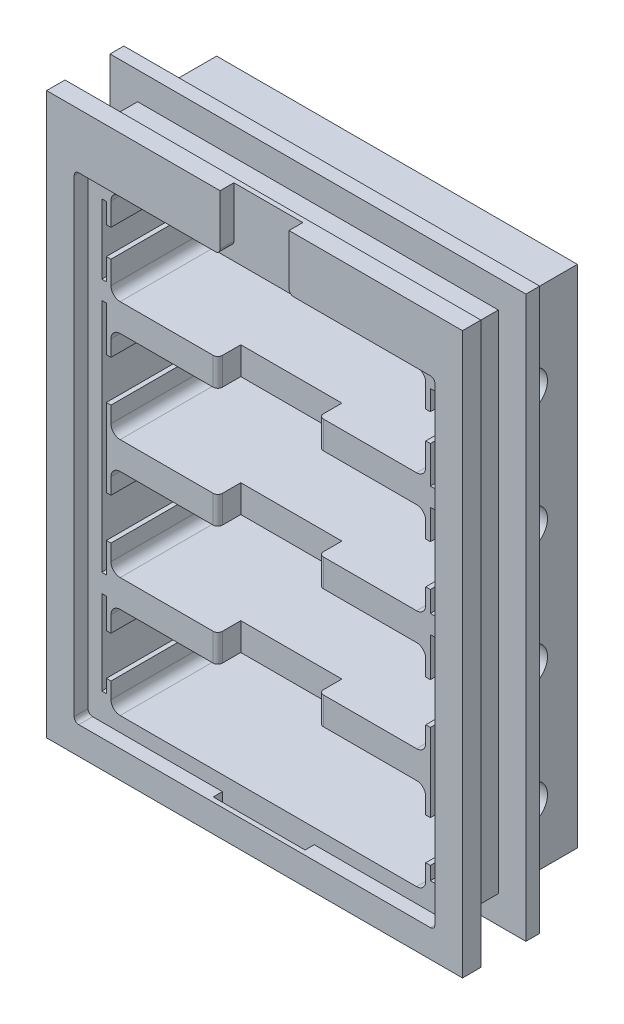
SolidWorks part; units mm, degrees
ref_plane "Front Plane" through (0, 0, 0) normal (0, 0, 1) x (1, 0, 0)
ref_plane "Top Plane" through (0, 0, 0) normal (0, 1, 0) x (1, 0, 0)
ref_plane "Right Plane" through (0, 0, 0) normal (1, 0, 0) x (0, 0, -1)
sketch "Sketch1" plane through (0, 0, 0) normal (0, 0, 1) x (1, 0, 0)
  line L0 (39.25, 52) -> (39.25, 26) construction
  line L2 (2.9994, 5.8357) -> (3.9994, 5.8357)
  line L4 (5.0006, 21.2207) -> (5.0006, 16.2207)
  line L5 (74.5018, 16.2207) -> (73.5006, 16.2207)
  line L6 (3.9994, 10.2207) -> (5.0006, 10.2207)
  line L7 (75.5018, 20.6057) -> (74.5018, 20.6057)
  line L12 (71.5006, 23.2207) -> (7.0006, 23.2207)
  line L13 (74.5018, 10.2207) -> (74.5018, 5.8357)
  line L15 (73.5006, 10.2207) -> (74.5018, 10.2207)
  line L17 (73.5006, 5.2207) -> (73.5006, 10.2207)
  line L18 (39.25, 0) -> (78.5, 0)
  line L19 (3.9994, 20.6057) -> (2.9994, 20.6057)
  line L20 (74.5018, 20.6057) -> (74.5018, 16.2207)
  line L21 (5.0006, 16.2207) -> (3.9994, 16.2207)
  line L22 (2.9994, 20.6057) -> (2.9994, 5.8357)
  line L23 (73.5006, 16.2207) -> (73.5006, 21.2207)
  line L24 (3.9994, 16.2207) -> (3.9994, 20.6057)
  line L25 (7.0006, 29.2207) -> (71.5006, 29.2207)
  line L26 (73.5006, 31.2207) -> (73.5006, 36.2207)
  line L27 (73.5006, 36.2207) -> (74.5018, 36.2207)
  line L28 (74.5018, 36.2207) -> (74.5018, 31.8357)
  line L29 (74.5018, 31.8357) -> (75.5018, 31.8357)
  line L30 (75.5018, 31.8357) -> (75.5018, 46.6057)
  line L31 (75.5018, 46.6057) -> (74.5018, 46.6057)
  line L32 (74.5018, 46.6057) -> (74.5018, 42.2207)
  line L33 (74.5018, 42.2207) -> (73.5006, 42.2207)
  line L34 (73.5006, 42.2207) -> (73.5006, 47.2207)
  line L35 (71.5006, 49.2207) -> (7.0006, 49.2207)
  line L36 (5.0006, 47.2207) -> (5.0006, 42.2207)
  line L37 (5.0006, 42.2207) -> (3.9994, 42.2207)
  line L38 (3.9994, 42.2207) -> (3.9994, 46.6057)
  line L39 (3.9994, 46.6057) -> (2.9994, 46.6057)
  line L40 (2.9994, 46.6057) -> (2.9994, 31.8357)
  line L41 (2.9994, 31.8357) -> (3.9994, 31.8357)
  line L42 (3.9994, 31.8357) -> (3.9994, 36.2207)
  line L43 (3.9994, 36.2207) -> (5.0006, 36.2207)
  line L44 (5.0006, 36.2207) -> (5.0006, 31.2207)
  line L45 (5.0006, 10.2207) -> (5.0006, 5.2207)
  line L46 (0, 0) -> (39.25, 0)
  line L47 (7.0006, 3.2207) -> (71.5006, 3.2207)
  line L48 (75.5018, 5.8357) -> (75.5018, 20.6057)
  line L49 (39.25, 26) -> (39.25, 0) construction
  line L50 (74.5018, 5.8357) -> (75.5018, 5.8357)
  line L51 (3.9994, 5.8357) -> (3.9994, 10.2207)
  line L56 (73.5006, 57.2207) -> (73.5006, 62.2207)
  line L60 (5.0006, 62.2207) -> (5.0006, 57.2207)
  line L61 (3.9994, 62.2207) -> (5.0006, 62.2207)
  line L62 (71.5006, 75.2208) -> (7.0006, 75.2208)
  line L63 (3.9994, 72.6057) -> (2.9994, 72.6057)
  line L64 (74.5018, 62.2207) -> (74.5018, 57.8357)
  line L65 (74.5018, 57.8357) -> (75.5018, 57.8357)
  line L66 (73.5006, 62.2207) -> (74.5018, 62.2207)
  line L67 (74.5018, 68.2207) -> (73.5006, 68.2207)
  line L68 (74.5018, 72.6057) -> (74.5018, 68.2207)
  line L69 (2.9994, 72.6057) -> (2.9994, 57.8357)
  line L70 (75.5018, 57.8357) -> (75.5018, 72.6057)
  line L71 (39.25, 55.2207) -> (39.25, 52) construction
  line L72 (3.9994, 68.2207) -> (3.9994, 72.6057)
  line L73 (5.0006, 73.2208) -> (5.0006, 68.2207)
  line L74 (73.5006, 68.2207) -> (73.5006, 73.2208)
  line L75 (75.5018, 72.6057) -> (74.5018, 72.6057)
  line L76 (0, 0) -> (0, 110)
  line L77 (78.5, 0) -> (78.5, 110)
  line L78 (7.0006, 55.2207) -> (71.5006, 55.2207)
  line L80 (3.9994, 57.8357) -> (3.9994, 62.2207)
  line L81 (5.0006, 68.2207) -> (3.9994, 68.2207)
  line L83 (2.9994, 57.8357) -> (3.9994, 57.8357)
  line L84 (39.25, 78) -> (39.25, 75.2208) construction
  line L85 (73.5006, 83.2208) -> (73.5006, 88.2207)
  line L89 (5.0006, 88.2207) -> (5.0006, 83.2208)
  line L90 (3.9994, 88.2207) -> (5.0006, 88.2207)
  line L91 (71.5006, 101.2208) -> (7.0006, 101.2208)
  line L92 (3.9994, 98.6058) -> (2.9994, 98.6058)
  line L93 (74.5018, 88.2207) -> (74.5018, 83.8358)
  line L94 (74.5018, 83.8358) -> (75.5018, 83.8358)
  line L95 (73.5006, 88.2207) -> (74.5018, 88.2207)
  line L96 (74.5018, 94.2207) -> (73.5006, 94.2207)
  line L97 (74.5018, 98.6058) -> (74.5018, 94.2207)
  line L98 (2.9994, 98.6058) -> (2.9994, 83.8358)
  line L99 (75.5018, 83.8358) -> (75.5018, 98.6058)
  line L101 (3.9994, 94.2207) -> (3.9994, 98.6058)
  line L102 (5.0006, 99.2208) -> (5.0006, 94.2207)
  line L103 (73.5006, 94.2207) -> (73.5006, 99.2208)
  line L104 (75.5018, 98.6058) -> (74.5018, 98.6058)
  line L107 (7.0006, 81.2208) -> (71.5006, 81.2208)
  line L109 (3.9994, 83.8358) -> (3.9994, 88.2207)
  line L110 (5.0006, 94.2207) -> (3.9994, 94.2207)
  line L112 (2.9994, 83.8358) -> (3.9994, 83.8358)
  line L113 (39.25, 81.2208) -> (39.25, 76.4408) construction
  line L115 (0, 110) -> (78.5, 110)
  arc A0 (7.0006, 23.2207) -> (5.0006, 21.2207) centre (7.0006, 21.2207) ccw
  arc A1 (5.0006, 5.2207) -> (7.0006, 3.2207) centre (7.0006, 5.2207) ccw
  arc A2 (73.5006, 21.2207) -> (71.5006, 23.2207) centre (71.5006, 21.2207) ccw
  arc A3 (71.5006, 3.2207) -> (73.5006, 5.2207) centre (71.5006, 5.2207) ccw
  arc A4 (71.5006, 29.2207) -> (73.5006, 31.2207) centre (71.5006, 31.2207) ccw
  arc A5 (73.5006, 47.2207) -> (71.5006, 49.2207) centre (71.5006, 47.2207) ccw
  arc A6 (7.0006, 49.2207) -> (5.0006, 47.2207) centre (7.0006, 47.2207) ccw
  arc A7 (5.0006, 31.2207) -> (7.0006, 29.2207) centre (7.0006, 31.2207) ccw
  arc A8 (5.0006, 57.2207) -> (7.0006, 55.2207) centre (7.0006, 57.2207) ccw
  arc A9 (7.0006, 75.2208) -> (5.0006, 73.2208) centre (7.0006, 73.2208) ccw
  arc A10 (71.5006, 55.2207) -> (73.5006, 57.2207) centre (71.5006, 57.2207) ccw
  arc A11 (73.5006, 73.2208) -> (71.5006, 75.2208) centre (71.5006, 73.2208) ccw
  arc A12 (5.0006, 83.2208) -> (7.0006, 81.2208) centre (7.0006, 83.2208) ccw
  arc A13 (7.0006, 101.2208) -> (5.0006, 99.2208) centre (7.0006, 99.2208) ccw
  arc A14 (71.5006, 81.2208) -> (73.5006, 83.2208) centre (71.5006, 83.2208) ccw
  arc A15 (73.5006, 99.2208) -> (71.5006, 101.2208) centre (71.5006, 99.2208) ccw
  circle A16 centre (39.25, 105.61) radius 1.55
  point P109 (39.25, 110)
  dimension "D3" = 4.39
  dimension "D1" = 110
  dimension "D2" = 78.5
  dimension "D4" = 6
  dimension "D5" = 6
extrude "Boss-Extrude1" add sketch "Sketch1" along normal blind 25
sketch "Sketch2" plane through (0, 0, 0) normal (0, 0, -1) x (-1, 0, 0)
  line L1 (-78.5, 110) -> (0, 110)
  line L2 (-78.5, 110) -> (-78.5, 0)
  line L3 (-78.5, 0) -> (0, 0)
  line L4 (0, 110) -> (0, 0)
  line L5 (0, 110) -> (-78.5, 110) construction
  line L6 (0, 0) -> (-78.5, 0) construction
extrude "Boss-Extrude2" add sketch "Sketch2" along normal blind 3
sketch "Sketch4" plane through (0, 0, 25) normal (0, 0, 1) x (1, 0, 0)
  line L13 (84.5, 116) -> (-6, 116)
  line L14 (-6, 116) -> (-6, -6)
  line L15 (-6, -6) -> (84.5, -6)
  line L16 (84.5, -6) -> (84.5, 116)
  line L17 (84.5, 116) -> (-6, 116)
  line L18 (-6, 116) -> (-6, -6)
  line L19 (-6, -6) -> (84.5, -6)
  line L20 (84.5, -6) -> (84.5, 116)
  line L23 (0, 110) -> (78.5, 110)
  line L24 (0, 110) -> (0, 0)
  line L25 (0, 0) -> (78.5, 0)
  line L26 (78.5, 110) -> (78.5, 0)
  dimension "D1" = 6
extrude "Boss-Extrude4" add sketch "Sketch4" along normal blind 3 and the other way blind 1 separate body
sketch "Sketch5" plane through (0, 0, 0) normal (0, 1, 0) x (1, 0, 0)
  line L1 (18.17, -25) -> (30.17, -25)
  line L2 (18.17, -25) -> (18.17, -22)
  line L3 (18.17, -22) -> (30.17, -22)
  line L4 (30.17, -25) -> (30.17, -22)
  line L5 (0, -28) -> (0, -24) construction
  line L6 (48.3367, -25) -> (60.3367, -25)
  line L7 (48.3367, -25) -> (48.3367, -27)
  line L8 (48.3367, -27) -> (60.3367, -27)
  line L9 (60.3367, -25) -> (60.3367, -27)
  line L10 (78.5, -28) -> (78.5, -24) construction
  line L12 (0, -25) -> (78.5, -25) construction
  point P12 (0, -26)
  point P15 (30.17, -23.5)
  dimension "D1" = 78.5
  dimension "D2" = 18.1667
  dimension "D3" = 18.17
  dimension "D4" = 2
extrude "Cut-Extrude1" cut sketch "Sketch5" against normal blind 4
sketch "Sketch6" plane through (0, 0, 25) normal (0, 0, 1) x (1, 0, 0)
  line L0 (2.9994, 57.8357) -> (2.9994, 46.6057)
  line L1 (2.9994, 83.8358) -> (3.9994, 83.8358)
  line L2 (2.9994, 83.8358) -> (2.9994, 72.6057)
  line L3 (2.9994, 72.6057) -> (3.9994, 72.6057)
  line L4 (3.9994, 83.8358) -> (3.9994, 72.6057)
  line L5 (3.9994, 57.8357) -> (3.9994, 46.6057)
  line L6 (2.9994, 46.6057) -> (3.9994, 46.6057)
  line L7 (2.9994, 57.8357) -> (3.9994, 57.8357)
  line L8 (2.9994, 31.8357) -> (2.9994, 20.6057)
  line L9 (3.9994, 31.8357) -> (3.9994, 20.6057)
  line L10 (2.9994, 20.6057) -> (3.9994, 20.6057)
  line L11 (2.9994, 31.8357) -> (3.9994, 31.8357)
  line L12 (74.5018, 83.8358) -> (74.5018, 72.6057)
  line L13 (75.5018, 83.8358) -> (75.5018, 72.6057)
  line L14 (74.5018, 72.6057) -> (75.5018, 72.6057)
  line L15 (74.5018, 83.8358) -> (75.5018, 83.8358)
  line L16 (74.5018, 57.8357) -> (74.5018, 46.6057)
  line L17 (75.5018, 57.8357) -> (75.5018, 46.6057)
  line L18 (74.5018, 46.6057) -> (75.5018, 46.6057)
  line L19 (74.5018, 57.8357) -> (75.5018, 57.8357)
  line L20 (74.5018, 31.8357) -> (74.5018, 20.6057)
  line L21 (75.5018, 31.8357) -> (75.5018, 20.6057)
  line L22 (74.5018, 20.6057) -> (75.5018, 20.6057)
  line L23 (74.5018, 31.8357) -> (75.5018, 31.8357)
extrude "Cut-Extrude2" cut sketch "Sketch6" against normal up to surface (25 mm away) up to face at (39.2506, 39.2207, 0)
sketch "Sketch10" plane through (2.9994, 0, 0) normal (1, 0, 0) x (0, 0, -1)
  line L0 (0, 98.6058) -> (0, 5.8357) construction
  line L1 (-25, 16.2207) -> (0, 16.2207) construction
  circle A0 centre (-7.5, 91.3401) radius 1.5
  circle A1 centre (-7.5, 65.3401) radius 1.5
  circle A2 centre (-7.5, 39.3401) radius 1.5
  circle A3 centre (-7.5, 13.3401) radius 1.5
  dimension "D1" = 7.5
  dimension "D2" = 26
  dimension "D3" = 26
  dimension "D4" = 3
  dimension "D5" = 3
  dimension "D6" = 3
  dimension "D7" = 3
  dimension "D8" = 7.5
  dimension "D9" = 7.5
  dimension "D10" = 7.5
  dimension "D11" = 26
extrude "Cut-Extrude3" cut sketch "Sketch10" against normal through all and the other way through all
sketch "Sketch14" plane through (0, 0, 0) normal (-1, 0, 0) x (0, 0, 1)
  circle A0 centre (7.5, 91.3401) radius 4
  circle A1 centre (7.5, 65.3401) radius 4
  circle A2 centre (7.5, 39.3401) radius 4
  circle A3 centre (7.5, 13.3401) radius 4
extrude "Cut-Extrude4" cut sketch "Sketch14" against normal blind 1.8
sketch "Sketch15" plane through (78.5, 0, 0) normal (1, 0, 0) x (0, 0, -1)
  circle A0 centre (-7.5, 91.3401) radius 4
  circle A1 centre (-7.5, 65.3401) radius 4
  circle A2 centre (-7.5, 39.3401) radius 4
  circle A3 centre (-7.5, 13.3401) radius 4
extrude "Cut-Extrude5" cut sketch "Sketch15" against normal blind 1.8
ref_plane "Plane1" through (0, 0, 14.2) normal (0, 0, -1) x (-1, 0, 0)
sketch "Sketch16" plane through (0, 0, 14.2) normal (0, 0, -1) x (-1, 0, 0)
  line L1 (-84.5, 116) -> (6, 116)
  line L2 (-84.5, 116) -> (-84.5, -6)
  line L3 (-84.5, -6) -> (6, -6)
  line L4 (6, 116) -> (6, -6)
  line L5 (-78.5, 110) -> (0, 110)
  line L6 (-78.5, 110) -> (-78.5, 0)
  line L7 (-78.5, 0) -> (0, 0)
  line L8 (0, 110) -> (0, 0)
extrude "Boss-Extrude5" add sketch "Sketch16" along normal blind 3
sketch "Sketch3" plane through (0, 0, 25) normal (0, 0, 1) x (1, 0, 0)
  line L4 (78.5, 0) -> (78.5, 104)
  line L5 (78.5, 104) -> (0, 104)
  line L6 (0, 104) -> (0, 0)
  line L7 (0, 0) -> (78.5, 0)
  line L8 (83.5, 115) -> (-5, 115)
  line L9 (83.5, 115) -> (-5, 115)
  line L10 (-5, 115) -> (-5, -5)
  line L11 (-5, -5) -> (83.5, -5)
  line L15 (-5, -5) -> (83.5, -5)
  line L16 (83.5, -5) -> (83.5, 109) construction
  line L17 (83.5, 109) -> (-5, 109) construction
  line L18 (-5, 109) -> (-5, -5) construction
  line L19 (-5, 115) -> (-5, -5)
  line L20 (83.5, -5) -> (83.5, 115)
  line L21 (83.5, -5) -> (83.5, 115)
  dimension "D1" = 5
  dimension "D2" = 5
extrude "Boss-Extrude3" add sketch "Sketch3" along normal blind 3
sketch "Sketch19" plane through (0, 0, 0) normal (0, 1, 0) x (1, 0, 0)
  line L0 (0, -25) -> (78.5, -25) construction
  line L1 (49.25, -25) -> (29.25, -25)
  line L2 (49.25, -25) -> (49.25, -27)
  line L3 (49.25, -27) -> (29.25, -27)
  line L4 (29.25, -25) -> (29.25, -27)
  line L6 (78.5, -24) -> (78.5, -28) construction
  dimension "D1" = 20
  dimension "D2" = 29.25
  dimension "D3" = 2
extrude "Cut-Extrude7" cut sketch "Sketch19" against normal through all
sketch "Sketch20" plane through (0, 0, 24) normal (0, 0, -1) x (-1, 0, 0)
  line L0 (-78.5, 0) -> (0, 0) construction
  line L1 (-31.3577, 0) -> (-8.4557, 0)
  line L2 (-31.3577, 0) -> (-31.3577, -5.864)
  line L3 (-31.3577, -5.864) -> (-8.4557, -5.864)
  line L4 (-8.4557, 0) -> (-8.4557, -5.864)
extrude "Boss-Extrude7" add sketch "Sketch20" against normal blind 1
sketch "Sketch21" plane through (0, 0, 28) normal (0, 0, 1) x (1, 0, 0)
  line L0 (78.5, 104) -> (0, 104) construction
  line L1 (31.75, 104) -> (46.75, 104)
  line L2 (31.75, 104) -> (31.75, 116)
  line L3 (31.75, 116) -> (46.75, 116)
  line L4 (46.75, 104) -> (46.75, 116)
  line L5 (84.5, 116) -> (-6, 116) construction
  line L6 (0, 104) -> (0, 0) construction
  dimension "D1" = 31.75
  dimension "D2" = 15
extrude "Cut-Extrude8" cut sketch "Sketch21" against normal up to surface (3 mm away) up to face at (39.25, 24.5, 25)
fillet "Fillet1" radius 1 6 edges at (0, 0, 26.5) (78.5, 0, 26.5) (0, 104, 26.5) (78.5, 104, 26.5) (31.75, 104, 26.5) (46.75, 104, 26.5)
sketch "Sketch17" plane through (0, 0, 28) normal (0, 0, 1) x (1, 0, 0)
  line L10 (1.3, 103.7) -> (31.05, 103.7)
  line L11 (32.05, 104.7) -> (32.05, 115.7)
  line L13 (46.45, 104.7) -> (46.45, 115.7)
  line L14 (47.45, 103.7) -> (77.2, 103.7)
  line L15 (78.2, 1.3) -> (78.2, 102.7)
  line L16 (1.3, 0.3) -> (77.2, 0.3)
  line L17 (0.3, 1.3) -> (0.3, 102.7)
  line L24 (32.05, 115.7) -> (32.05, 116)
  line L25 (32.05, 116) -> (46.45, 116)
  line L26 (46.45, 116) -> (46.45, 115.7)
  circle A0 centre (39.25, 110) radius 2
  arc A1 (31.05, 103.7) -> (32.05, 104.7) centre (31.05, 104.7) ccw
  arc A2 (46.45, 104.7) -> (47.45, 103.7) centre (47.45, 104.7) ccw
  arc A3 (1.3, 0.3) -> (0.3, 1.3) centre (1.3, 1.3) cw
  arc A4 (78.2, 1.3) -> (77.2, 0.3) centre (77.2, 1.3) cw
  arc A5 (77.2, 103.7) -> (78.2, 102.7) centre (77.2, 102.7) cw
  arc A6 (1.3, 103.7) -> (0.3, 102.7) centre (1.3, 102.7) ccw
  dimension "D3" = 4
  dimension "D1" = 1
  dimension "D2" = 1
extrude "Boss-Extrude6" add sketch "Sketch17" along normal blind 5
sketch "Sketch18" plane through (0, 0, 28) normal (0, 0, 1) x (1, 0, 0)
  line L1 (-18.6224, 121.4355) -> (97.7501, 121.4355)
  line L2 (-18.6224, 121.4355) -> (-18.6224, -9.8758)
  line L3 (-18.6224, -9.8758) -> (97.7501, -9.8758)
  line L4 (97.7501, 121.4355) -> (97.7501, -9.8758)
extrude "Cut-Extrude6" cut sketch "Sketch18" along normal blind 2 contours L2 L1 L4 L3
sketch "Sketch22" plane through (0, 0.3, 0) normal (0, -1, 0) x (1, 0, 0)
  line L0 (77.2, 30) -> (1.3, 30) construction
  line L1 (29.75, 30) -> (48.75, 30)
  line L2 (29.75, 30) -> (29.75, 31.8)
  line L3 (29.75, 31.8) -> (48.75, 31.8)
  line L4 (48.75, 30) -> (48.75, 31.8)
  line L5 (0.3, 33) -> (0.3, 30) construction
  dimension "D1" = 29.45
  dimension "D2" = 19
  dimension "D3" = 1.8
extrude "Boss-Extrude8" add sketch "Sketch22" along normal blind 4
fillet "Fillet2" radius 0.5 2 edges at (48.75, -3.7, 30.9) (29.75, -3.7, 30.9)
sketch "Sketch23" plane through (0, 0, 28) normal (0, 0, 1) x (1, 0, 0)
  line L1 (-19.0302, 123.3512) -> (108.9774, 123.3512)
  line L2 (-19.0302, 123.3512) -> (-19.0302, -13.955)
  line L3 (-19.0302, -13.955) -> (108.9774, -13.955)
  line L4 (108.9774, 123.3512) -> (108.9774, -13.955)
extrude "Cut-Extrude9" cut sketch "Sketch23" along normal through all
sketch "Sketch24" plane through (0, 0, 25) normal (0, 0, 1) x (1, 0, 0)
  circle A0 centre (39.25, 105.61) radius 3.0484
extrude "Boss-Extrude9" add sketch "Sketch24" against normal blind 4
sketch "Sketch25" plane through (0, 0, 25) normal (0, 0, 1) x (1, 0, 0)
  line L0 (74.5018, 62.2207) -> (74.5018, 42.2207) construction
  line L1 (74.5018, 52.2207) -> (75.5018, 52.2207)
  line L2 (74.5018, 52.2207) -> (74.5018, 56.2207)
  line L3 (74.5018, 56.2207) -> (75.5018, 56.2207)
  line L4 (75.5018, 52.2207) -> (75.5018, 56.2207)
  line L5 (75.5018, 5.8357) -> (75.5018, 98.6058) construction
  line L7 (3.9994, 16.2207) -> (3.9994, 36.2207) construction
  line L8 (3.9994, 28.2207) -> (2.9994, 28.2207)
  line L9 (3.9994, 28.2207) -> (3.9994, 24.2207)
  line L10 (3.9994, 24.2207) -> (2.9994, 24.2207)
  line L11 (2.9994, 28.2207) -> (2.9994, 24.2207)
  line L12 (2.9994, 98.6058) -> (2.9994, 5.8357) construction
  line L13 (7.0006, 29.2207) -> (71.5006, 29.2207) construction
  line L15 (71.5006, 23.2207) -> (7.0006, 23.2207) construction
  line L16 (3.9994, 68.2207) -> (3.9994, 88.2207) construction
  line L17 (3.9994, 79.4581) -> (2.9994, 79.4581)
  line L18 (3.9994, 79.4581) -> (3.9994, 83.4581)
  line L19 (3.9994, 83.4581) -> (2.9994, 83.4581)
  line L20 (2.9994, 79.4581) -> (2.9994, 83.4581)
  line L21 (2.9994, 98.6058) -> (2.9994, 5.8357) construction
  line L22 (74.5018, 88.2207) -> (74.5018, 68.2207) construction
  line L23 (74.5018, 80.2208) -> (75.5018, 80.2208)
  line L24 (74.5018, 80.2208) -> (74.5018, 76.2208)
  line L25 (74.5018, 76.2208) -> (75.5018, 76.2208)
  line L26 (75.5018, 80.2208) -> (75.5018, 76.2208)
  line L27 (7.0006, 81.2208) -> (71.5006, 81.2208) construction
  dimension "D1" = 4
  dimension "D2" = 1
  dimension "D3" = 1
  dimension "D4" = 4
  dimension "D5" = 1
  dimension "D6" = 4
extrude "Boss-Extrude10" add sketch "Sketch25" against normal up to surface (25 mm away) up to face at (39.2506, 52.2207, 0)
sketch "Sketch26" plane through (0, 0, 0) normal (0, 0, 1) x (1, 0, 0)
  line L0 (2.9994, 24.2207) -> (2.9994, 5.8357) construction
  line L1 (2.9994, 15.3407) -> (4.9994, 15.3407)
  line L2 (2.9994, 15.3407) -> (2.9994, 11.3407)
  line L3 (2.9994, 11.3407) -> (4.9994, 11.3407)
  line L4 (4.9994, 15.3407) -> (4.9994, 11.3407)
  line L6 (4.5, 16.2207) -> (4.5, 13.3407) construction
  line L8 (5.0006, 16.2207) -> (3.9994, 16.2207) construction
  line L9 (4.5, 13.3407) -> (6.6042, 13.3407) construction
  line L10 (73.5018, 67.3407) -> (75.5018, 67.3407)
  line L11 (74.0012, 68.2207) -> (74.0012, 65.3407) construction
  line L12 (75.5018, 67.3407) -> (75.5018, 63.3407)
  line L13 (74.0012, 65.3407) -> (76.1054, 65.3407) construction
  line L14 (73.5018, 67.3407) -> (73.5018, 63.3407)
  line L15 (73.5018, 63.3407) -> (75.5018, 63.3407)
  line L16 (75.5018, 56.2207) -> (75.5018, 76.2208) construction
  point P10 (4.9994, 13.3407)
  dimension "D1" = 4
  dimension "D2" = 2
  dimension "D3" = 2.88
  dimension "D4" = 4
  dimension "D5" = 2
extrude "Cut-Extrude10" cut sketch "Sketch26" against normal blind 10
sketch "Sketch27" plane through (0, 0, 25) normal (0, 0, 1) x (1, 0, 0)
  line L0 (5.0006, 10.2207) -> (5.0006, 5.2207) construction
  line L1 (3.9994, 10.2207) -> (5.0006, 10.2207)
  line L2 (3.9994, 10.2207) -> (3.9994, 8.7207)
  line L3 (3.9994, 8.7207) -> (5.0006, 8.7207)
  line L4 (5.0006, 10.2207) -> (5.0006, 8.7207)
  line L5 (73.5006, 8.7207) -> (74.5018, 8.7207)
  line L6 (73.5006, 10.2207) -> (73.5006, 8.7207)
  line L7 (73.5006, 10.2207) -> (74.5018, 10.2207)
  line L8 (74.5018, 10.2207) -> (74.5018, 8.7207)
  line L9 (73.5006, 34.7207) -> (74.5018, 34.7207)
  line L10 (73.5006, 36.2207) -> (73.5006, 34.7207)
  line L11 (73.5006, 36.2207) -> (74.5018, 36.2207)
  line L12 (74.5018, 36.2207) -> (74.5018, 34.7207)
  line L13 (3.9994, 34.7207) -> (5.0006, 34.7207)
  line L14 (3.9994, 36.2207) -> (3.9994, 34.7207)
  line L15 (3.9994, 36.2207) -> (5.0006, 36.2207)
  line L16 (5.0006, 36.2207) -> (5.0006, 34.7207)
  line L17 (3.9994, 60.7207) -> (5.0006, 60.7207)
  line L18 (3.9994, 62.2207) -> (3.9994, 60.7207)
  line L19 (3.9994, 62.2207) -> (5.0006, 62.2207)
  line L20 (5.0006, 62.2207) -> (5.0006, 60.7207)
  line L21 (73.5006, 60.7207) -> (74.5018, 60.7207)
  line L22 (73.5006, 62.2207) -> (73.5006, 60.7207)
  line L23 (73.5006, 62.2207) -> (74.5018, 62.2207)
  line L24 (74.5018, 62.2207) -> (74.5018, 60.7207)
  line L25 (3.9994, 16.2207) -> (5.0006, 16.2207)
  line L26 (5.0006, 17.7207) -> (5.0006, 16.2207)
  line L27 (74.5018, 17.7207) -> (74.5018, 16.2207)
  line L28 (73.5006, 17.7207) -> (74.5018, 17.7207)
  line L29 (3.9994, 17.7207) -> (5.0006, 17.7207)
  line L30 (3.9994, 17.7207) -> (3.9994, 16.2207)
  line L31 (73.5006, 17.7207) -> (73.5006, 16.2207)
  line L32 (73.5006, 16.2207) -> (74.5018, 16.2207)
  line L33 (3.9994, 42.2207) -> (5.0006, 42.2207)
  line L34 (5.0006, 43.7207) -> (5.0006, 42.2207)
  line L35 (74.5018, 43.7207) -> (74.5018, 42.2207)
  line L36 (73.5006, 43.7207) -> (74.5018, 43.7207)
  line L37 (3.9994, 43.7207) -> (5.0006, 43.7207)
  line L38 (3.9994, 43.7207) -> (3.9994, 42.2207)
  line L39 (73.5006, 43.7207) -> (73.5006, 42.2207)
  line L40 (73.5006, 42.2207) -> (74.5018, 42.2207)
  line L41 (3.9994, 68.2207) -> (5.0006, 68.2207)
  line L42 (5.0006, 69.7207) -> (5.0006, 68.2207)
  line L43 (74.5018, 69.7207) -> (74.5018, 68.2207)
  line L44 (73.5006, 69.7207) -> (74.5018, 69.7207)
  line L45 (3.9994, 69.7207) -> (5.0006, 69.7207)
  line L46 (3.9994, 69.7207) -> (3.9994, 68.2207)
  line L47 (73.5006, 69.7207) -> (73.5006, 68.2207)
  line L48 (73.5006, 68.2207) -> (74.5018, 68.2207)
  dimension "D1" = 1.5
extrude "Cut-Extrude11" cut sketch "Sketch27" against normal up to surface (25 mm away) up to face at (39.2506, 39.636, 0)
sketch "Sketch28" plane through (0, 0, 25) normal (0, 0, 1) x (1, 0, 0)
  line L0 (7.0006, 81.2208) -> (71.5006, 81.2208) construction
  line L2 (28.2506, 81.2208) -> (28.2506, 75.2208)
  line L3 (28.2506, 75.2208) -> (50.2506, 75.2208)
  line L4 (50.2506, 81.2208) -> (50.2506, 75.2208)
  line L5 (71.5006, 75.2208) -> (7.0006, 75.2208) construction
  line L6 (39.2506, 81.2208) -> (39.2506, 75.2208) construction
  line L7 (7.0006, 81.2208) -> (71.5006, 81.2208) construction
  line L8 (28.2506, 81.2208) -> (50.2506, 81.2208)
  line L9 (28.2506, 55.2207) -> (28.2506, 49.2207)
  line L10 (28.2506, 49.2207) -> (50.2506, 49.2207)
  line L11 (28.2506, 55.2207) -> (50.2506, 55.2207)
  line L12 (50.2506, 55.2207) -> (50.2506, 49.2207)
  line L13 (39.2506, 55.2207) -> (39.2506, 49.2207) construction
  line L14 (28.2506, 29.2207) -> (28.2506, 23.2207)
  line L15 (28.2506, 23.2207) -> (50.2506, 23.2207)
  line L16 (28.2506, 29.2207) -> (50.2506, 29.2207)
  line L17 (50.2506, 29.2207) -> (50.2506, 23.2207)
  line L18 (39.2506, 29.2207) -> (39.2506, 23.2207) construction
  dimension "D1" = 22
  dimension "D2" = 11
extrude "Cut-Extrude12" cut sketch "Sketch28" against normal blind 5
fillet "Fillet3" radius 1 6 edges at (50.2506, 78.2208, 25) (50.2506, 52.2207, 25) (50.2506, 26.2207, 25) (28.2506, 26.2207, 25) (28.2506, 52.2207, 25) (28.2506, 78.2208, 25)
